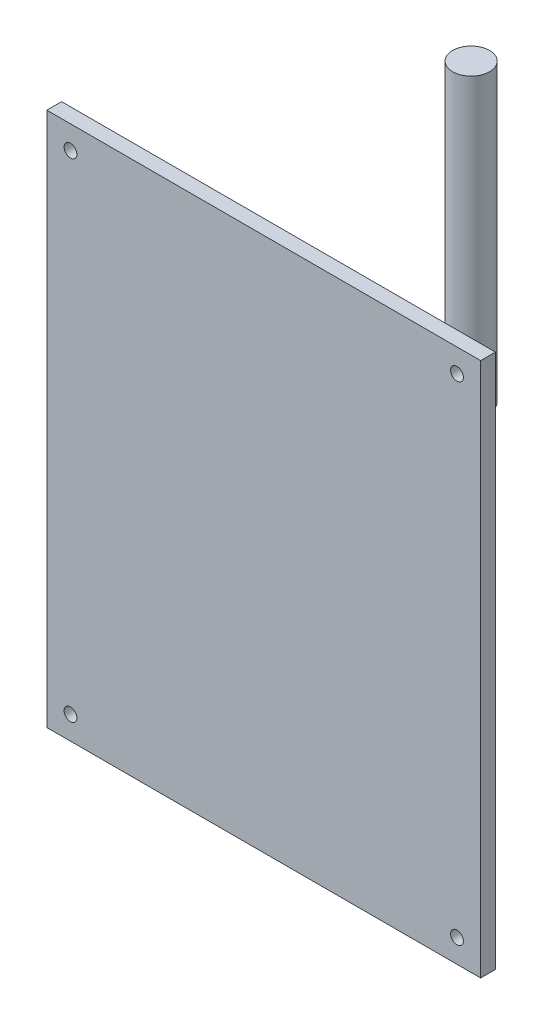
SolidWorks part; units mm, degrees
material "Copper"
ref_plane "Front Plane" through (0, 0, 0) normal (0, 0, 1) x (1, 0, 0)
ref_plane "Top Plane" through (0, 0, 0) normal (0, 1, 0) x (1, 0, 0)
ref_plane "Right Plane" through (0, 0, 0) normal (1, 0, 0) x (0, 0, -1)
sketch "Sketch1" plane through (0, 0, 0) normal (0, 0, 1) x (1, 0, 0)
  line L1 (-37.325, -46) -> (37.325, -46)
  line L2 (-37.325, -46) -> (-37.325, 46)
  line L3 (-37.325, 46) -> (37.325, 46)
  line L4 (37.325, -46) -> (37.325, 46)
  line L5 (-37.325, -46) -> (37.325, 46) construction
  line L6 (-37.325, 46) -> (37.325, -46) construction
  point P0 (0, 0)
  dimension "D1" = 92
  dimension "D2" = 74.65
extrude "Boss-Extrude1" add sketch "Sketch1" along normal blind 2.54 contours L3 L4 L1 L2
sketch "Sketch2" plane through (0, 46, 0) normal (0, 1, 0) x (1, 0, 0)
  line L0 (-37.325, 0) -> (37.325, 0) construction
  circle A0 centre (29.964, 3.175) radius 3.175
  dimension "D1" = 6.35
extrude "Boss-Extrude2" add sketch "Sketch2" along normal blind 38.1 and the other way blind 12.7 separate body
sketch "Sketch3" plane through (0, 0, 2.54) normal (0, 0, 1) x (1, 0, 0)
  line L4 (-33.25, 42) -> (33.25, 42) construction
  line L5 (0, 42) -> (0, 0) construction
  line L6 (-33.25, 42) -> (-33.25, -42) construction
  line L7 (-33.25, 0) -> (0, 0) construction
  circle A0 centre (-33.25, 42) radius 1.1
  circle A1 centre (33.25, 42) radius 1.1
  circle A2 centre (33.25, -42) radius 1.1
  circle A3 centre (-33.25, -42) radius 1.1
  dimension "D1" = 2.2
  dimension "D2" = 84
  dimension "D3" = 66.5
extrude "Cut-Extrude1" cut sketch "Sketch3" against normal up to surface (2.54 mm away) up to face at (0, 0, 0)
